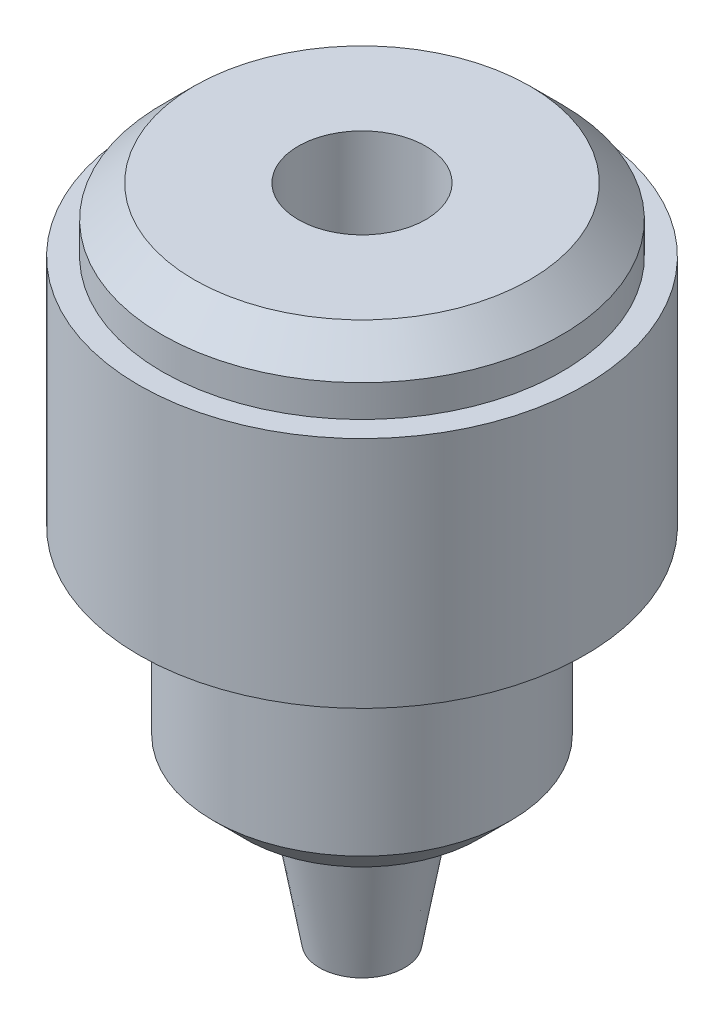
SolidWorks part; units mm, degrees
ref_plane "Спереди" through (0, 0, 0) normal (0, 0, 1) x (1, 0, 0)
ref_plane "Сверху" through (0, 0, 0) normal (0, 1, 0) x (1, 0, 0)
ref_plane "Справа" through (0, 0, 0) normal (1, 0, 0) x (0, 0, -1)
sketch "Эскиз1" plane through (0, 0, 0) normal (0, 1, 0) x (1, 0, 0)
  circle A0 centre (0, 0) radius 10.5
extrude "Бобышка-Вытянуть1" add sketch "Эскиз1" against normal blind 28 contours A0
sketch "Эскиз4" plane through (0, 0, 0) normal (0, 1, 0) x (1, 0, 0)
  circle A0 centre (0, 0) radius 9.4
extrude "Бобышка-Вытянуть3" add sketch "Эскиз4" along normal blind 3
chamfer "Фаска2" distance 1.5 angle 45 1 edges at (0, 3, 9.4)
sketch "Эскиз5" plane through (0, 3, 0) normal (0, 1, 0) x (1, 0, 0)
  circle A0 centre (0, 0) radius 3
extrude "Вырез-Вытянуть2" cut sketch "Эскиз5" against normal blind 14
sketch "Эскиз6" plane through (0, -28, 0) normal (0, -1, 0) x (1, 0, 0)
  circle A0 centre (0, 0) radius 7
  circle A1 centre (0, 0) radius 10.5
extrude "Вырез-Вытянуть3" cut sketch "Эскиз6" against normal blind 17
sketch "Эскиз7" plane through (0, -28, 0) normal (0, -1, 0) x (1, 0, 0)
  circle A0 centre (0, 0) radius 2
  circle A1 centre (0, 0) radius 7
  dimension "D1" = 4
extrude "Вырез-Вытянуть4" cut sketch "Эскиз7" against normal blind 7
chamfer "Фаска3" distance 1.5 angle 45 1 edges at (0, -21, -7)
draft "Уклон3" type of draft neutral plane draft angle 10 faces to draft 1 face at (0, -21, -2) neutral plane through (0, -28, 0) neutral plane normal (0, -1, 0) parameters "D1"=10
